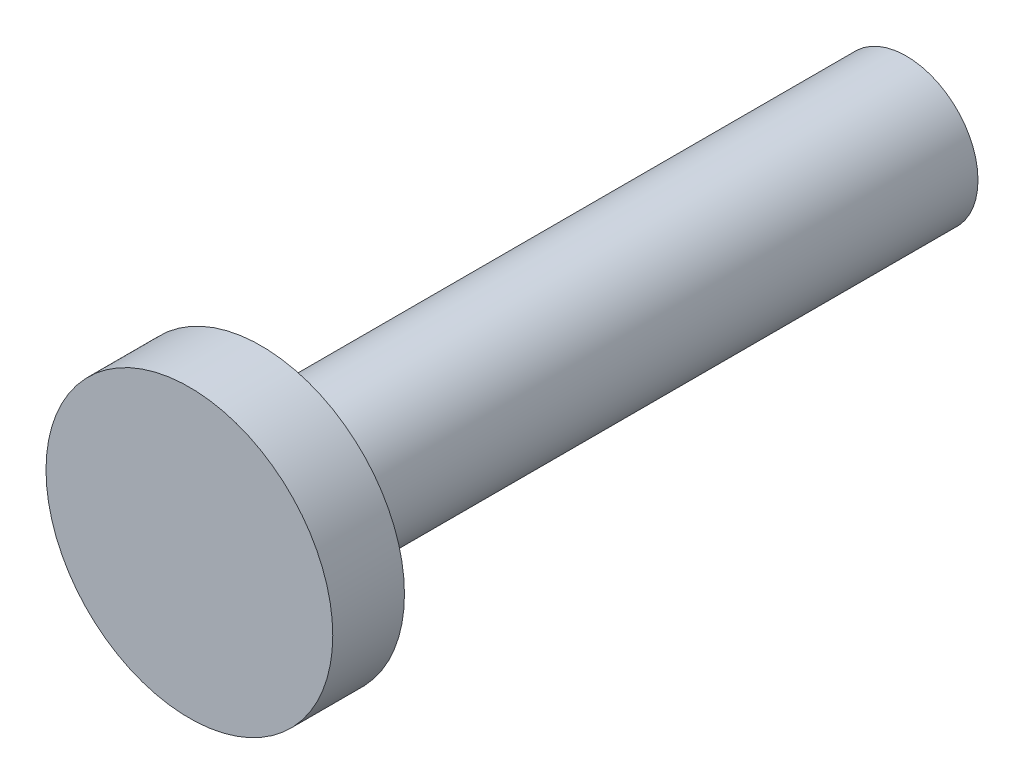
SolidWorks part; units mm, degrees
ref_plane "Front Plane" through (0, 0, 0) normal (0, 0, 1) x (1, 0, 0)
ref_plane "Top Plane" through (0, 0, 0) normal (0, 1, 0) x (1, 0, 0)
ref_plane "Right Plane" through (0, 0, 0) normal (1, 0, 0) x (0, 0, -1)
sketch "Sketch1" plane through (0, 0, 0) normal (0, 0, 1) x (1, 0, 0)
  circle A0 centre (0, 0) radius 10
  dimension "D1" = 20
extrude "Boss-Extrude1" add sketch "Sketch1" along normal blind 5
sketch "Sketch2" plane through (0, 0, 0) normal (0, 0, -1) x (-1, 0, 0)
  circle A0 centre (0, 0) radius 5
  dimension "D1" = 10
extrude "Boss-Extrude2" add sketch "Sketch2" along normal blind 45
